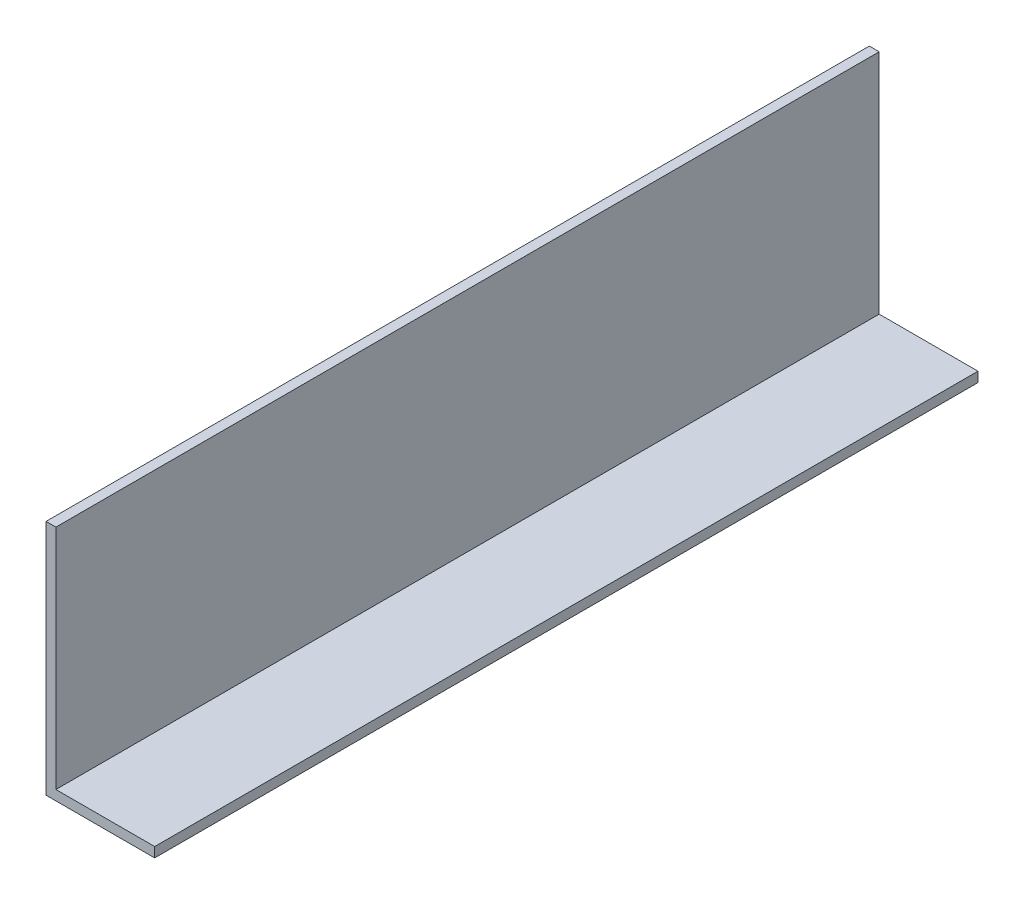
SolidWorks part; units mm, degrees
ref_plane "Front Plane" through (0, 0, 0) normal (0, 0, 1) x (1, 0, 0)
ref_plane "Top Plane" through (0, 0, 0) normal (0, 1, 0) x (1, 0, 0)
ref_plane "Right Plane" through (0, 0, 0) normal (1, 0, 0) x (0, 0, -1)
sketch "Sketch1" plane through (0, 0, 0) normal (0, 0, 1) x (1, 0, 0)
  line L0 (0, 72) -> (3, 72)
  line L1 (3, 3) -> (3, 72)
  line L9 (0, 72) -> (0, 0)
  line L10 (0, 0) -> (33, 0)
  line L11 (33, 0) -> (33, 3)
  line L12 (33, 3) -> (3, 3)
  dimension "D7" = 30
  dimension "D1" = 3
  dimension "D2" = 3
  dimension "D3" = 72
extrude "Boss-Extrude1" add sketch "Sketch1" along normal blind 250 contours L9 L10 L11 L12 L1 L0
equation "\"D2@Sketch1\"=\"D1@Sketch1\""
